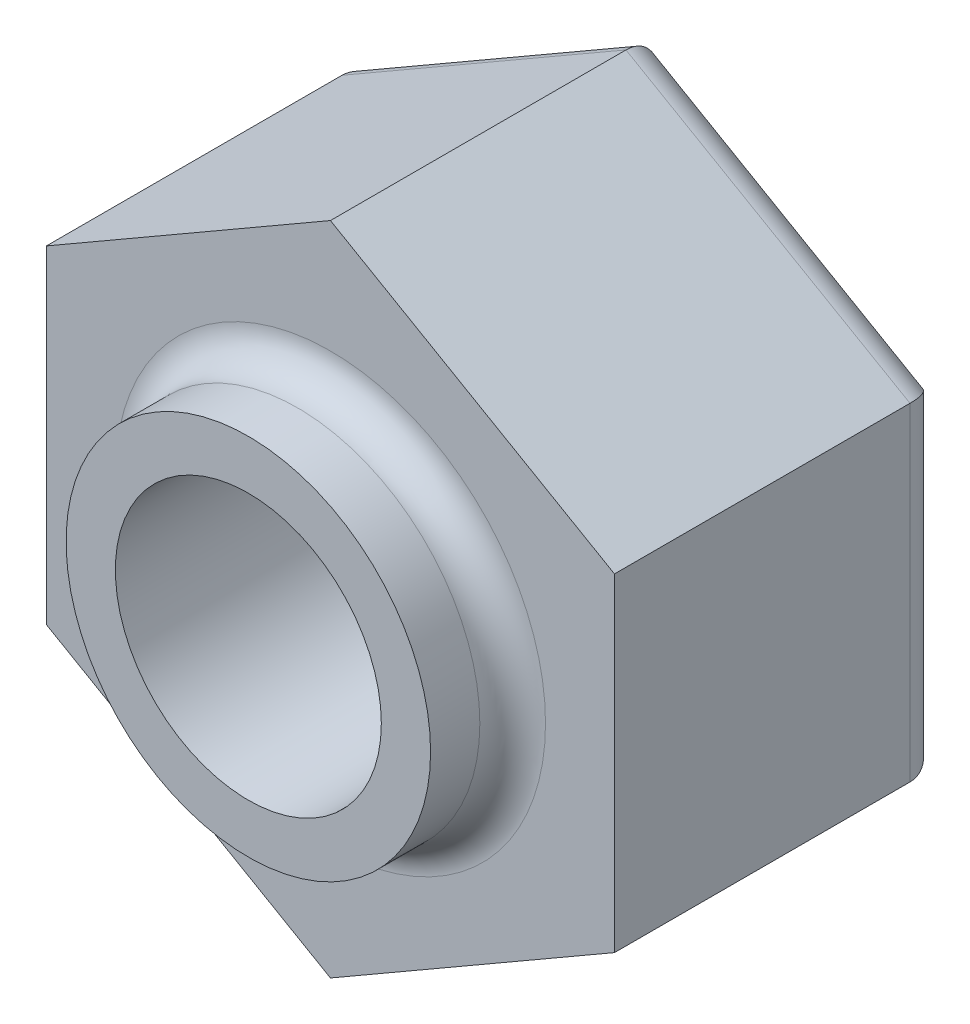
SolidWorks part; units mm, degrees
ref_plane "Front Plane" through (0, 0, 0) normal (0, 0, 1) x (1, 0, 0)
ref_plane "Top Plane" through (0, 0, 0) normal (0, 1, 0) x (1, 0, 0)
ref_plane "Right Plane" through (0, 0, 0) normal (1, 0, 0) x (0, 0, -1)
sketch "Sketch1" plane through (0, 0, 0) normal (0, 0, 1) x (1, 0, 0)
  line L1 (8.65, -4.9941) -> (8.65, 4.9941)
  line L2 (8.65, 4.9941) -> (0, 9.9882)
  line L3 (0, 9.9882) -> (-8.65, 4.9941)
  line L4 (-8.65, 4.9941) -> (-8.65, -4.9941)
  line L5 (-8.65, -4.9941) -> (0, -9.9882)
  line L6 (0, -9.9882) -> (8.65, -4.9941)
  circle A0 centre (0, 0) radius 8.65 construction
  circle A1 centre (0, 0) radius 4.05
  dimension "D1" = 17.3
  dimension "D2" = 8.1
extrude "Boss-Extrude1" add sketch "Sketch1" along normal blind 10
sketch "Sketch2" plane through (0, 0, 10) normal (0, 0, 1) x (1, 0, 0)
  circle A0 centre (0, 0) radius 5.55
  circle A1 centre (0, 0) radius 4.05 construction
  circle M7 centre (0, 0) radius 4.05
  dimension "D1" = 1.5
extrude "Boss-Extrude2" add sketch "Sketch2" along normal blind 2.5 contours A0 M7
fillet "Fillet1" radius 1 8 edges at (5.55, 0, 10) (4.05, 0, 0) (8.65, 0, 0) (4.325, 7.4911, 0) (-4.325, 7.4911, 0) (-8.65, 0, 0) (-4.325, -7.4911, 0) (4.325, -7.4911, 0)
